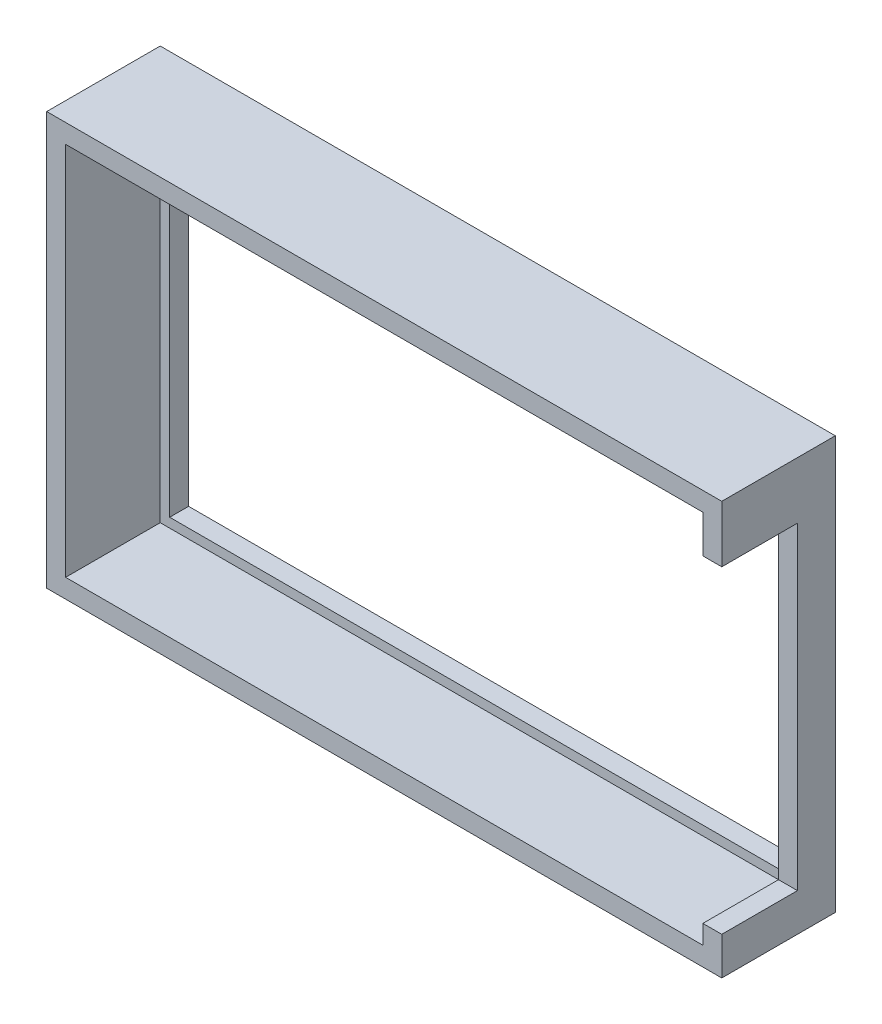
SolidWorks part; units mm, degrees
ref_plane "Plan de face" through (0, 0, 0) normal (0, 0, 1) x (1, 0, 0)
ref_plane "Plan de dessus" through (0, 0, 0) normal (0, 1, 0) x (1, 0, 0)
ref_plane "Plan de droite" through (0, 0, 0) normal (1, 0, 0) x (0, 0, -1)
sketch "Esquisse1" plane through (0, 0, 0) normal (0, 0, 1) x (1, 0, 0)
  line L1 (0, 0) -> (35.68, 0)
  line L2 (0, 0) -> (0, 21.82)
  line L3 (0, 21.82) -> (35.68, 21.82)
  line L4 (35.68, 0) -> (35.68, 21.82)
extrude "Boss.-Extru.1" add sketch "Esquisse1" along normal blind 6
sketch "Esquisse2" plane through (0, 0, 6) normal (0, 0, 1) x (1, 0, 0)
  line L0 (0, 0) -> (35.68, 0) construction
  line L1 (1, 1) -> (34.68, 1)
  line L2 (1, 1) -> (1, 20.82)
  line L3 (1, 20.82) -> (34.68, 20.82)
  line L4 (34.68, 1) -> (34.68, 20.82)
  line L5 (0, 21.82) -> (0, 0) construction
  line L6 (35.68, 21.82) -> (0, 21.82) construction
  line L7 (35.68, 0) -> (35.68, 21.82) construction
  dimension "D1" = 1
  dimension "D2" = 1
  dimension "D3" = 1
  dimension "D4" = 1
extrude "Enlèv. mat.-Extru.1" cut sketch "Esquisse2" against normal blind 5
sketch "Esquisse3" plane through (0, 0, 1) normal (0, 0, 1) x (1, 0, 0)
  line L1 (1.5, 1.5) -> (34.18, 1.5)
  line L2 (1.5, 1.5) -> (1.5, 20.32)
  line L3 (1.5, 20.32) -> (34.18, 20.32)
  line L4 (34.18, 1.5) -> (34.18, 20.32)
  line L5 (1, 1) -> (34.68, 1) construction
  line L6 (1, 20.82) -> (1, 1) construction
  line L7 (34.68, 1) -> (34.68, 20.82) construction
  line L8 (34.68, 20.82) -> (1, 20.82) construction
  dimension "D1" = 0.5
  dimension "D2" = 0.5
  dimension "D3" = 0.5
  dimension "D4" = 0.5
extrude "Enlèv. mat.-Extru.2" cut sketch "Esquisse3" against normal through all
sketch "Esquisse4" plane through (35.68, 0, 0) normal (1, 0, 0) x (0, 0, -1)
  line L0 (-6, 0) -> (-6, 21.82) construction
  line L1 (-6, 18.82) -> (-2, 18.82)
  line L2 (-6, 18.82) -> (-6, 2)
  line L3 (-6, 2) -> (-2, 2)
  line L4 (-2, 18.82) -> (-2, 2)
  line L5 (-6, 0) -> (0, 0) construction
  line L6 (-6, 21.82) -> (0, 21.82) construction
  line L7 (0, 0) -> (0, 21.82) construction
  dimension "D1" = 0
  dimension "D2" = 2
  dimension "D3" = 3
  dimension "D4" = 2
extrude "Enlèv. mat.-Extru.3" cut sketch "Esquisse4" against normal blind 5
sketch "Esquisse5" plane through (0, 0, 1) normal (0, 0, 1) x (1, 0, 0)
  line L0 (35.68, 21.82) -> (0, 21.82) construction
  line L1 (34.18, 20.82) -> (34.68, 20.82)
  line L2 (34.18, 20.82) -> (34.18, 20.32)
  line L3 (34.18, 20.32) -> (34.68, 20.32)
  line L4 (34.68, 20.82) -> (34.68, 20.32)
  line L5 (35.68, 2) -> (35.68, 18.82) construction
  line L6 (34.18, 20.32) -> (1.5, 20.32) construction
  line L7 (34.18, 1.5) -> (34.18, 20.32) construction
  dimension "D1" = 1
  dimension "D2" = 1
  dimension "D3" = 0
  dimension "D4" = 0
